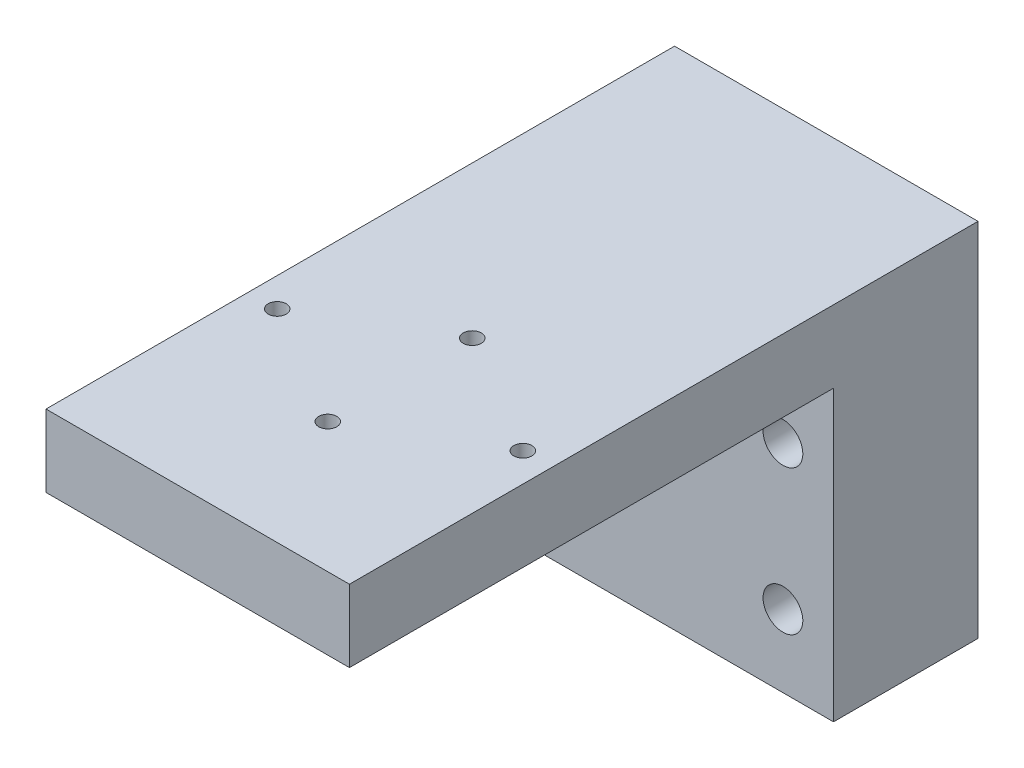
SolidWorks part; units mm, degrees
material "铝材"
ref_plane "前基準面" through (0, 0, 0) normal (0, 0, 1) x (1, 0, 0)
ref_plane "上基準面" through (0, 0, 0) normal (0, 1, 0) x (1, 0, 0)
ref_plane "右基準面" through (0, 0, 0) normal (1, 0, 0) x (0, 0, -1)
sketch "草图1" plane through (0, 0, 0) normal (0, 0, 1) x (1, 0, 0)
  line L1 (0, 0) -> (42, 0)
  line L2 (0, 0) -> (0, 50)
  line L3 (0, 50) -> (42, 50)
  line L4 (42, 0) -> (42, 50)
  dimension "D1" = 42
  dimension "D2" = 50
extrude "凸台-拉伸1" add sketch "草图1" along normal blind 87
sketch "草图2" plane through (42, 0, 0) normal (1, 0, 0) x (0, 0, -1)
  line L0 (-87, 50) -> (0, 50) construction
  line L1 (-87, 0) -> (-20, 0)
  line L2 (-87, 0) -> (-87, 40)
  line L3 (-87, 40) -> (-20, 40)
  line L4 (-20, 0) -> (-20, 40)
  line L5 (0, 0) -> (0, 50) construction
  dimension "D1" = 10
  dimension "D2" = 20
extrude "切除-拉伸1" cut sketch "草图2" against normal through all
sketch "草图3" plane through (0, 0, 20) normal (0, 0, 1) x (1, 0, 0)
  line L0 (21, 0) -> (21, 40) construction
  line L1 (0, 0) -> (42, 0) construction
  line L2 (0, 40) -> (42, 40) construction
  circle A0 centre (7, 30) radius 2.75
  circle A1 centre (7, 10) radius 2.75
  circle A2 centre (35, 10) radius 2.75
  circle A3 centre (35, 30) radius 2.75
  dimension "D1" = 5.5
  dimension "D2" = 10
  dimension "D3" = 20
  dimension "D4" = 28
extrude "切除-拉伸2" cut sketch "草图3" against normal through all
hole_wizard "M3 螺纹孔1" positions "草图5" profile "草图4" tap size "M3" standard "ISO"
sketch "草图5" plane through (0, 50, 0) normal (0, 1, 0) x (-1, 0, 0)
  point P1 (-4, 59)
  point P4 (-21, 49)
  point P7 (-38, 59)
  point P10 (-21, 69)
sketch "草图4" plane through (4, 50, 59) normal (1, 0, 0) x (0, 0, 1)
  line L0 (0, 0) -> (0, 8.2511)
  line L1 (0, 8.2511) -> (1.25, 7.5)
  line L2 (1.25, 7.5) -> (1.25, 0)
  line L5 (1.25, 0) -> (0, 0)
  line L10 (0, 8.2511) -> (-1.25, 7.5) construction
  line L11 (0, -6.35) -> (0, 107.95) construction
  dimension "螺纹孔钻头直径" = 2.5
  dimension "螺纹孔钻头深度" = 7.5
  dimension "导头角度" = 118
cosmetic thread "孔螺蚊线1" parameters "D1"=6, "D2"=3
cosmetic thread "孔螺蚊线2" parameters "D1"=6, "D2"=3
cosmetic thread "孔螺蚊线3" parameters "D1"=6, "D2"=3
cosmetic thread "孔螺蚊线4" parameters "D1"=6, "D2"=3
